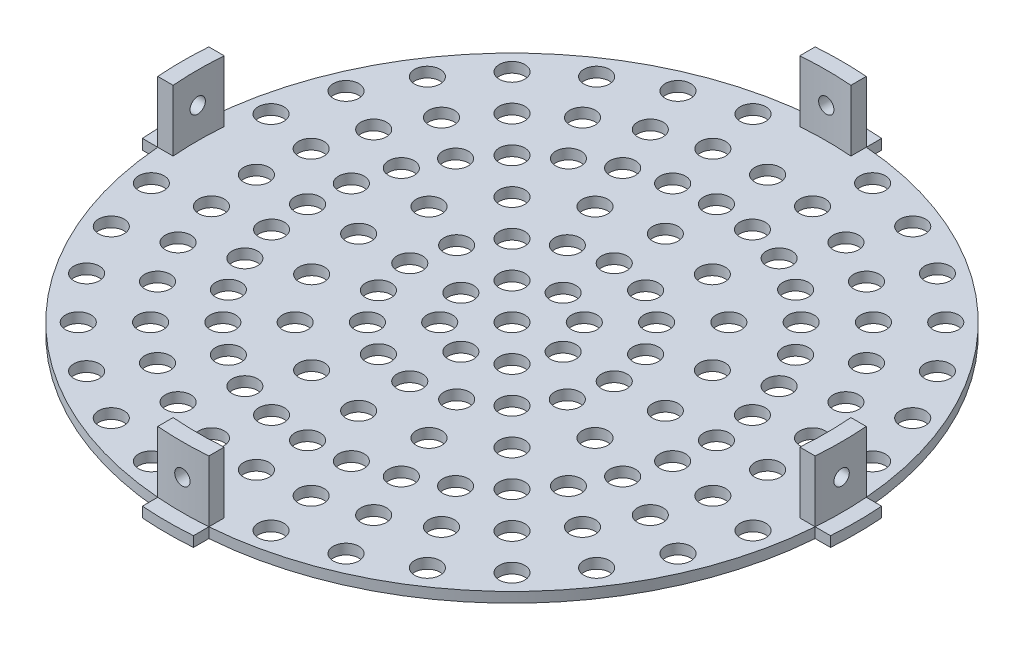
SolidWorks part; units mm, degrees
material "ПК/АБС"
ref_plane "Спереди" through (0, 0, 0) normal (0, 0, 1) x (1, 0, 0)
ref_plane "Сверху" through (0, 0, 0) normal (0, 1, 0) x (1, 0, 0)
ref_plane "Справа" through (0, 0, 0) normal (1, 0, 0) x (0, 0, -1)
sketch "Эскиз1" plane through (0, 0, 0) normal (0, 0, 1) x (1, 0, 0)
  line L0 (0, 0) -> (0, 31.0108) construction
  line L1 (0, 0) -> (-67.5, 0)
  line L2 (-67.5, 0) -> (-67.5, 2)
  line L3 (-67.5, 2) -> (-64.5, 2)
  line L4 (-64.5, 2) -> (-64.5, 14)
  line L5 (-64.5, 14) -> (-61.5, 14)
  line L6 (-61.5, 14) -> (-61.5, 2)
  line L7 (-61.5, 2) -> (0, 2)
  line L8 (0, 2) -> (0, 0)
  line L9 (-61.5, 2) -> (-64.5, 2) construction
  dimension "D1" = 135
  dimension "D2" = 129
  dimension "D3" = 2
  dimension "D4" = 14
  dimension "D5" = 123
revolve "Повернуть1" add sketch "Эскиз1" angle 360 about L0
sketch "Эскиз2" plane through (0, 0, 0) normal (0, 1, 0) x (1, 0, 0)
  line L0 (0, 0) -> (-99.0051, 0) construction
  line L1 (-67.3146, 5) -> (-64.3059, 5)
  line L2 (-67.3146, -5) -> (-64.3059, -5)
  line L3 (5, 67.3146) -> (5, 64.3059)
  line L4 (-5, 67.3146) -> (-5, 64.3059)
  line L5 (67.3146, -5) -> (64.3059, -5)
  line L6 (67.3146, 5) -> (64.3059, 5)
  line L7 (-5, -67.3146) -> (-5, -64.3059)
  line L8 (5, -67.3146) -> (5, -64.3059)
  circle A0 centre (0, 0) radius 64.5
  circle A1 centre (0, 0) radius 67.5
  point P24 (0, 0)
  dimension "D1" = 129
  dimension "D2" = 135
  dimension "D3" = 10
  dimension "D4" = 4
extrude "Вырез-Вытянуть2" cut sketch "Эскиз2" along normal blind 10 contours L4 A1 L1 A0 | L6 A1 L3 A0 | L8 A1 L5 A0 | L2 A1 L7 A0
sketch "Эскиз3" plane through (0, 0, 0) normal (0, 1, 0) x (1, 0, 0)
  circle A0 centre (0, 0) radius 2.5
  circle A1 centre (0, 0) radius 10 construction
  circle A2 centre (0, 10) radius 2.5
  circle A3 centre (0, 0) radius 20 construction
  circle A4 centre (0, 20) radius 2.5
  circle A5 centre (0, 0) radius 30 construction
  circle A6 centre (0, 30) radius 2.5
  circle A7 centre (0, 0) radius 40 construction
  circle A8 centre (0, 40) radius 2.5
  circle A9 centre (0, 0) radius 50 construction
  circle A10 centre (0, 50) radius 2.5
  circle A11 centre (0, 0) radius 60 construction
  circle A14 centre (0, 60) radius 2.5 construction
  circle A15 centre (7.0711, 7.0711) radius 2.5
  circle A16 centre (10, 0) radius 2.5
  circle A17 centre (7.0711, -7.0711) radius 2.5
  circle A18 centre (0, -10) radius 2.5
  circle A19 centre (-7.0711, -7.0711) radius 2.5
  circle A20 centre (-10, 0) radius 2.5
  circle A21 centre (-7.0711, 7.0711) radius 2.5
  circle A22 centre (7.6537, 18.4776) radius 2.5
  circle A23 centre (14.1421, 14.1421) radius 2.5
  circle A24 centre (18.4776, 7.6537) radius 2.5
  circle A25 centre (20, 0) radius 2.5
  circle A26 centre (18.4776, -7.6537) radius 2.5
  circle A27 centre (14.1421, -14.1421) radius 2.5
  circle A28 centre (7.6537, -18.4776) radius 2.5
  circle A29 centre (0, -20) radius 2.5
  circle A30 centre (-7.6537, -18.4776) radius 2.5
  circle A31 centre (-14.1421, -14.1421) radius 2.5
  circle A32 centre (-18.4776, -7.6537) radius 2.5
  circle A33 centre (-20, 0) radius 2.5
  circle A34 centre (-18.4776, 7.6537) radius 2.5
  circle A35 centre (-14.1421, 14.1421) radius 2.5
  circle A36 centre (-7.6537, 18.4776) radius 2.5
  circle A37 centre (11.4805, 27.7164) radius 2.5
  circle A38 centre (21.2132, 21.2132) radius 2.5
  circle A39 centre (27.7164, 11.4805) radius 2.5
  circle A40 centre (30, 0) radius 2.5
  circle A41 centre (27.7164, -11.4805) radius 2.5
  circle A42 centre (21.2132, -21.2132) radius 2.5
  circle A43 centre (11.4805, -27.7164) radius 2.5
  circle A44 centre (0, -30) radius 2.5
  circle A45 centre (-11.4805, -27.7164) radius 2.5
  circle A46 centre (-21.2132, -21.2132) radius 2.5
  circle A47 centre (-27.7164, -11.4805) radius 2.5
  circle A48 centre (-30, 0) radius 2.5
  circle A49 centre (-27.7164, 11.4805) radius 2.5
  circle A50 centre (-21.2132, 21.2132) radius 2.5
  circle A51 centre (-11.4805, 27.7164) radius 2.5
  circle A52 centre (-7.8036, 39.2314) radius 2.5
  circle A53 centre (-9.7545, 49.0393) radius 2.5
  circle A54 centre (-15.3073, 36.9552) radius 2.5
  circle A55 centre (-19.1342, 46.194) radius 2.5
  circle A56 centre (-22.2228, 33.2588) radius 2.5
  circle A57 centre (-27.7785, 41.5735) radius 2.5
  circle A58 centre (-28.2843, 28.2843) radius 2.5
  circle A59 centre (-35.3553, 35.3553) radius 2.5
  circle A60 centre (-33.2588, 22.2228) radius 2.5
  circle A61 centre (-41.5735, 27.7785) radius 2.5
  circle A62 centre (-36.9552, 15.3073) radius 2.5
  circle A63 centre (-46.194, 19.1342) radius 2.5
  circle A64 centre (-39.2314, 7.8036) radius 2.5
  circle A65 centre (-49.0393, 9.7545) radius 2.5
  circle A66 centre (-40, 0) radius 2.5
  circle A67 centre (-50, 0) radius 2.5
  circle A68 centre (-39.2314, -7.8036) radius 2.5
  circle A69 centre (-49.0393, -9.7545) radius 2.5
  circle A70 centre (-36.9552, -15.3073) radius 2.5
  circle A71 centre (-46.194, -19.1342) radius 2.5
  circle A72 centre (-33.2588, -22.2228) radius 2.5
  circle A73 centre (-41.5735, -27.7785) radius 2.5
  circle A74 centre (-28.2843, -28.2843) radius 2.5
  circle A75 centre (-35.3553, -35.3553) radius 2.5
  circle A76 centre (-22.2228, -33.2588) radius 2.5
  circle A77 centre (-27.7785, -41.5735) radius 2.5
  circle A78 centre (-15.3073, -36.9552) radius 2.5
  circle A79 centre (-19.1342, -46.194) radius 2.5
  circle A80 centre (-7.8036, -39.2314) radius 2.5
  circle A81 centre (-9.7545, -49.0393) radius 2.5
  circle A82 centre (0, -40) radius 2.5
  circle A83 centre (0, -50) radius 2.5
  circle A84 centre (7.8036, -39.2314) radius 2.5
  circle A85 centre (9.7545, -49.0393) radius 2.5
  circle A86 centre (15.3073, -36.9552) radius 2.5
  circle A87 centre (19.1342, -46.194) radius 2.5
  circle A88 centre (22.2228, -33.2588) radius 2.5
  circle A89 centre (27.7785, -41.5735) radius 2.5
  circle A90 centre (28.2843, -28.2843) radius 2.5
  circle A91 centre (35.3553, -35.3553) radius 2.5
  circle A92 centre (33.2588, -22.2228) radius 2.5
  circle A93 centre (41.5735, -27.7785) radius 2.5
  circle A94 centre (36.9552, -15.3073) radius 2.5
  circle A95 centre (46.194, -19.1342) radius 2.5
  circle A96 centre (39.2314, -7.8036) radius 2.5
  circle A97 centre (49.0393, -9.7545) radius 2.5
  circle A98 centre (40, 0) radius 2.5
  circle A99 centre (50, 0) radius 2.5
  circle A100 centre (39.2314, 7.8036) radius 2.5
  circle A101 centre (49.0393, 9.7545) radius 2.5
  circle A102 centre (36.9552, 15.3073) radius 2.5
  circle A103 centre (46.194, 19.1342) radius 2.5
  circle A104 centre (33.2588, 22.2228) radius 2.5
  circle A105 centre (41.5735, 27.7785) radius 2.5
  circle A106 centre (28.2843, 28.2843) radius 2.5
  circle A107 centre (35.3553, 35.3553) radius 2.5
  circle A108 centre (22.2228, 33.2588) radius 2.5
  circle A109 centre (27.7785, 41.5735) radius 2.5
  circle A110 centre (15.3073, 36.9552) radius 2.5
  circle A111 centre (19.1342, 46.194) radius 2.5
  circle A112 centre (7.8036, 39.2314) radius 2.5
  circle A113 centre (9.7545, 49.0393) radius 2.5
  circle A114 centre (-11.7054, 58.8471) radius 2.5
  circle A115 centre (-22.961, 55.4328) radius 2.5
  circle A116 centre (-33.3342, 49.8882) radius 2.5
  circle A117 centre (-42.4264, 42.4264) radius 2.5
  circle A118 centre (-49.8882, 33.3342) radius 2.5
  circle A119 centre (-55.4328, 22.961) radius 2.5
  circle A120 centre (-58.8471, 11.7054) radius 2.5
  circle A121 centre (-60, 0) radius 2.5 construction
  circle A122 centre (-58.8471, -11.7054) radius 2.5
  circle A123 centre (-55.4328, -22.961) radius 2.5
  circle A124 centre (-49.8882, -33.3342) radius 2.5
  circle A125 centre (-42.4264, -42.4264) radius 2.5
  circle A126 centre (-33.3342, -49.8882) radius 2.5
  circle A127 centre (-22.961, -55.4328) radius 2.5
  circle A128 centre (-11.7054, -58.8471) radius 2.5
  circle A129 centre (0, -60) radius 2.5 construction
  circle A130 centre (11.7054, -58.8471) radius 2.5
  circle A131 centre (22.961, -55.4328) radius 2.5
  circle A132 centre (33.3342, -49.8882) radius 2.5
  circle A133 centre (42.4264, -42.4264) radius 2.5
  circle A134 centre (49.8882, -33.3342) radius 2.5
  circle A135 centre (55.4328, -22.961) radius 2.5
  circle A136 centre (58.8471, -11.7054) radius 2.5
  circle A137 centre (60, 0) radius 2.5 construction
  circle A138 centre (58.8471, 11.7054) radius 2.5
  circle A139 centre (55.4328, 22.961) radius 2.5
  circle A140 centre (49.8882, 33.3342) radius 2.5
  circle A141 centre (42.4264, 42.4264) radius 2.5
  circle A142 centre (33.3342, 49.8882) radius 2.5
  circle A143 centre (22.961, 55.4328) radius 2.5
  circle A144 centre (11.7054, 58.8471) radius 2.5
  point P37 (0, 0)
  point P41 (0, 0)
  point P44 (0, 0)
  point P47 (0, 0)
  point P50 (0, 0)
  point P53 (0, 0)
  point P56 (0, 0)
  point P59 (0, 0)
  point P62 (0, 0)
  point P65 (0, 0)
  point P68 (0, 0)
  point P71 (0, 0)
  point P74 (0, 0)
  point P77 (0, 0)
  point P80 (0, 0)
  point P83 (0, 0)
  point P84 (0, 0)
  point P86 (0, 0)
  point P89 (0, 0)
  point P92 (0, 0)
  point P95 (0, 0)
  point P98 (0, 0)
  point P101 (0, 0)
  point P104 (0, 0)
  point P107 (0, 0)
  point P110 (0, 0)
  point P113 (0, 0)
  point P116 (0, 0)
  point P119 (0, 0)
  point P122 (0, 0)
  point P125 (0, 0)
  point P128 (0, 0)
  point P129 (0, 0)
  point P285 (0, 0)
  dimension "D1" = 5
  dimension "D2" = 20
  dimension "D3" = 5
  dimension "D4" = 40
  dimension "D5" = 60
  dimension "D6" = 80
  dimension "D7" = 100
  dimension "D8" = 120
  dimension "D9" = 5
  dimension "D10" = 5
  dimension "D11" = 5
  dimension "D12" = 5
  dimension "D13" = 5
  dimension "D14" = 8
  dimension "D15" = 16
  dimension "D16" = 16
  dimension "D17" = 32
extrude "Вырез-Вытянуть4" cut sketch "Эскиз3" along normal through all
sketch "Эскиз4" plane through (0, 14, 0) normal (0, 1, 0) x (1, 0, 0)
  line L0 (-64.3059, 5) -> (-61.2964, 5)
  line L1 (-67.5, 0) -> (-56.6158, 0) construction
  line L2 (-64.3059, -5) -> (-61.2964, -5)
  line L3 (5, 64.3059) -> (5, 61.2964)
  line L4 (-5, 64.3059) -> (-5, 61.2964)
  line L5 (64.3059, -5) -> (61.2964, -5)
  line L6 (64.3059, 5) -> (61.2964, 5)
  line L7 (-5, -64.3059) -> (-5, -61.2964)
  line L8 (5, -64.3059) -> (5, -61.2964)
  circle A0 centre (0, 0) radius 61.5
  circle A1 centre (0, 0) radius 64.5
  arc A2 (-67.3146, 5) -> (-67.3146, -5) centre (0, 0) ccw construction
  point P29 (0, 0)
  dimension "D1" = 123
  dimension "D2" = 129
  dimension "D3" = 10
  dimension "D4" = 4
extrude "Вырез-Вытянуть5" cut sketch "Эскиз4" against normal blind 12 contours L4 A1 L0 A0 | L6 A1 L3 A0 | L8 A1 L5 A0 | L2 A1 L7 A0
sketch "Эскиз5" plane through (0, 0, 0) normal (0, 0, 1) x (1, 0, 0)
  line L0 (0, 2) -> (0, 8) construction
  line L1 (5, 2) -> (-5, 2) construction
  circle A0 centre (0, 8) radius 1.5
  dimension "D1" = 3
  dimension "D2" = 6
extrude "Вырез-Вытянуть6" cut sketch "Эскиз5" against normal through all
pattern_circular "Круговой массив1" count 4 over 360 about axis through (0, 0, 0) along (0, -1, 0) of "Вырез-Вытянуть6"
